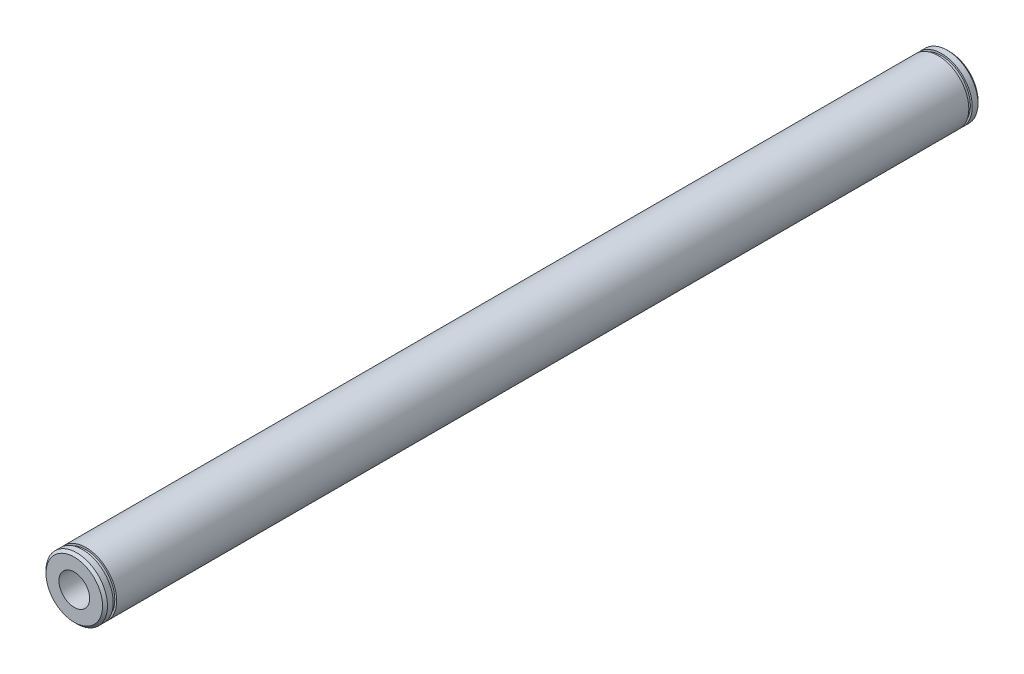
SolidWorks part; units mm, degrees
material "AISI 4130 Steel, annealed at 865C"
ref_plane "Front Plane" through (0, 0, 0) normal (0, 0, 1) x (1, 0, 0)
ref_plane "Top Plane" through (0, 0, 0) normal (0, 1, 0) x (1, 0, 0)
ref_plane "Right Plane" through (0, 0, 0) normal (1, 0, 0) x (0, 0, -1)
sketch "Sketch1" plane through (0, 0, 0) normal (0, 0, 1) x (1, 0, 0)
  circle A0 centre (0, 0) radius 9.525
  circle A1 centre (0, 0) radius 4.7498
  dimension "D1" = 19.05
  dimension "D2" = 9.4996
extrude "Boss-Extrude1" add sketch "Sketch1" along normal mid plane 263.906
sketch "Sketch2" plane through (0, 0, 131.953) normal (0, 0, 1) x (1, 0, 0)
  circle A0 centre (0, 0) radius 8.9408
  circle A1 centre (0, 0) radius 4.7498
  dimension "D1" = 9.4996
  dimension "D2" = 17.8816
extrude "Boss-Extrude2" add sketch "Sketch2" along normal blind 1.0668
sketch "Sketch4" plane through (0, 0, 133.0198) normal (0, 0, 1) x (1, 0, 0)
  circle A0 centre (0, 0) radius 9.525
  circle A1 centre (0, 0) radius 9.525 construction
  circle A2 centre (0, 0) radius 4.7498
  circle A3 centre (0, 0) radius 4.7498 construction
extrude "Boss-Extrude4" add sketch "Sketch4" along normal blind 2.54
chamfer "Chamfer1" distance 0.762 angle 45 1 edges at (9.525, 0, 135.5598)
mirror "Mirror1" about plane through (0, 0, 0) normal (0, 0, 1) of "Boss-Extrude2", "Boss-Extrude4", "Chamfer1"
